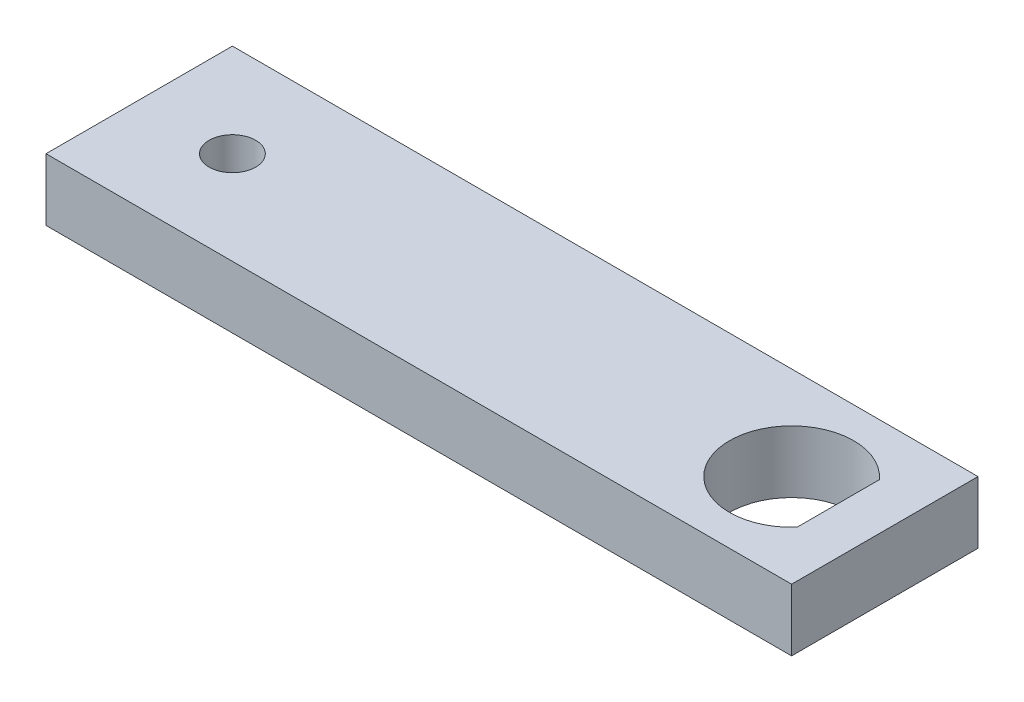
SolidWorks part; units mm, degrees
ref_plane "Front" through (0, 0, 0) normal (0, 0, 1) x (1, 0, 0)
ref_plane "Top" through (0, 0, 0) normal (0, 1, 0) x (-1, 0, 0)
ref_plane "Right" through (0, 0, 0) normal (1, 0, 0) x (0, 0, -1)
sketch "Sketch1" plane through (0, 0, 0) normal (0, 0, 1) x (1, 0, 0)
  line L0 (0, 0) -> (76.2, 0)
  line L1 (0, 0) -> (0, 6.35)
  line L2 (76.2, 6.35) -> (0, 6.35)
  line L3 (76.2, 6.35) -> (76.2, 0)
  dimension "D1" = 6.35
  dimension "D2" = 76.2
extrude "Base-Extrude" add sketch "Sketch1" along normal blind 19.05
sketch "Sketch2" plane through (0, 6.35, 0) normal (0, 1, 0) x (-1, 0, 0)
  line L0 (-76.2, 19.05) -> (-76.2, 0) construction
  line L1 (-76.2, 19.05) -> (0, 19.05) construction
  line L2 (-71.4375, 5.3249) -> (-71.4375, 13.7251)
  arc A0 (-71.4375, 5.3249) -> (-71.4375, 13.7251) centre (-66.675, 9.525) ccw
  dimension "D1" = 12.7
  dimension "D2" = 9.525
  dimension "D3" = 9.525
  dimension "D4" = 1.5875
extrude "Cut-Extrude1" cut sketch "Sketch2" against normal through all
sketch "Sketch3" plane through (0, 6.35, 0) normal (0, 1, 0) x (-1, 0, 0)
  line L0 (0, 19.05) -> (0, 0) construction
  circle A0 centre (-9.525, 9.525) radius 2.3813
  arc A1 (-71.4375, 5.3249) -> (-71.4375, 13.7251) centre (-66.675, 9.525) ccw construction
  point P5 (-66.675, 9.525)
  dimension "D1" = 4.7625
  dimension "D2" = 9.525
extrude "Cut-Extrude2" cut sketch "Sketch3" against normal through all
sketch "Sketch4" plane through (0, 0, 0) normal (0, 1, 0) x (-1, 0, 0)
  line L0 (-76.2, 0) -> (0, 0) construction
  line L1 (-76.2, 19.05) -> (0, 19.05) construction
  line L2 (-66.675, 19.05) -> (-79.375, 19.05)
  line L3 (-79.375, 19.05) -> (-79.375, 0)
  line L4 (-79.375, 0) -> (-66.675, 0)
  line L5 (-9.525, 19.05) -> (3.175, 19.05)
  line L6 (3.175, 19.05) -> (3.175, 0)
  line L7 (3.175, 0) -> (-9.525, 0)
  line L8 (0, 19.05) -> (0, 0) construction
  line L9 (-76.2, 19.05) -> (-76.2, 0) construction
  line L10 (0, 19.05) -> (-76.2, 19.05) construction
  arc A0 (-66.675, 0) -> (-66.675, 19.05) centre (-66.675, 9.525) cw
  arc A1 (-9.525, 19.05) -> (-9.525, 0) centre (-9.525, 9.525) cw
  dimension "D2" = 3.175
  dimension "D1" = 3.175
extrude "Cut-Extrude3" [suppressed] cut sketch "Sketch4" along normal up to next
